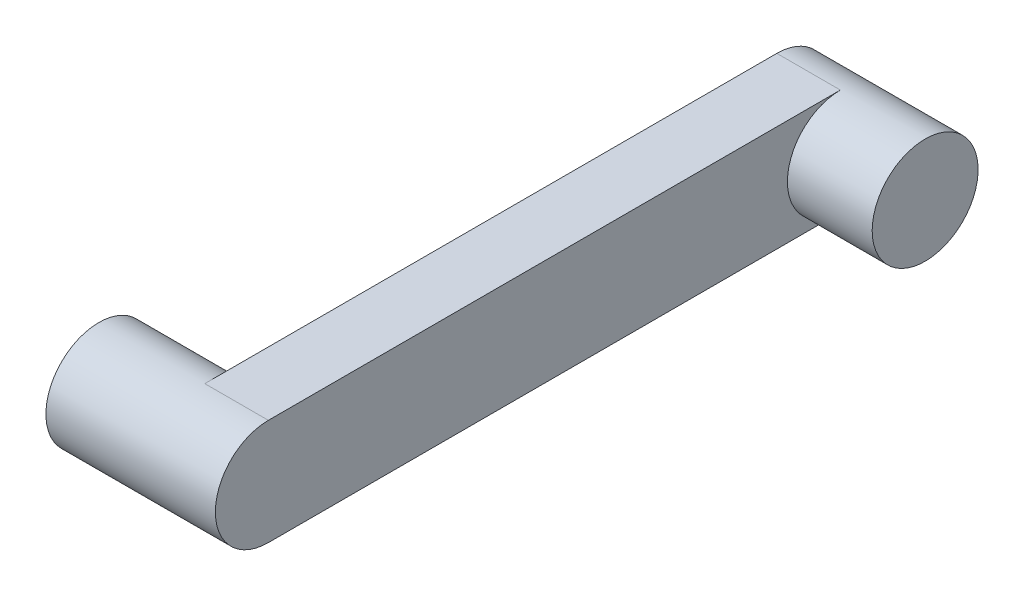
SolidWorks part; units mm, degrees
ref_plane "Front Plane" through (0, 0, 0) normal (0, 0, 1) x (1, 0, 0)
ref_plane "Top Plane" through (0, 0, 0) normal (0, 1, 0) x (1, 0, 0)
ref_plane "Right Plane" through (0, 0, 0) normal (1, 0, 0) x (0, 0, -1)
sketch "Sketch1" plane through (0, 0, 0) normal (1, 0, 0) x (0, 0, -1)
  line L1 (-13.5, -2.5) -> (13.5, -2.5)
  line L2 (-13.5, -2.5) -> (-13.5, 2.5)
  line L3 (-13.5, 2.5) -> (13.5, 2.5)
  line L4 (13.5, -2.5) -> (13.5, 2.5)
  line L5 (-13.5, -2.5) -> (13.5, 2.5) construction
  line L6 (-13.5, 2.5) -> (13.5, -2.5) construction
  point P0 (0, 0)
  dimension "D1" = 27
  dimension "D2" = 5
extrude "Boss-Extrude1" add sketch "Sketch1" along normal blind 3
sketch "Sketch2" plane through (3, 0, 0) normal (1, 0, 0) x (0, 0, -1)
  line L0 (-13.5, 2.5) -> (-13.5, -2.5) construction
  circle A0 centre (-13.5, 0) radius 2.5
extrude "Boss-Extrude2" add sketch "Sketch2" against normal blind 8
sketch "Sketch3" plane through (0, 0, 0) normal (-1, 0, 0) x (0, 0, 1)
  line L0 (-13.5, -2.5) -> (-13.5, 2.5) construction
  circle A0 centre (-13.5, 0) radius 2.5
extrude "Boss-Extrude3" add sketch "Sketch3" against normal blind 7
